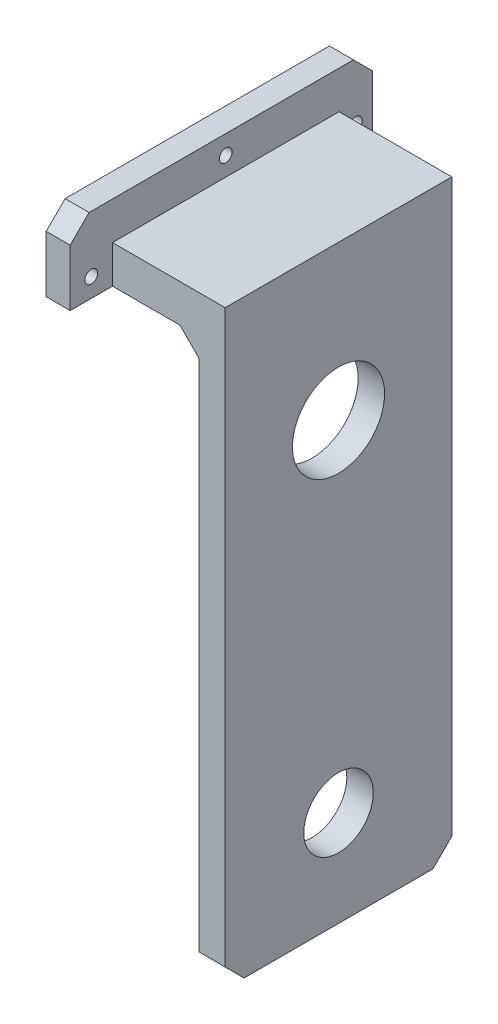
SolidWorks part; units mm, degrees
material "PLA"
ref_plane "Front Plane" through (0, 0, 0) normal (0, 0, 1) x (1, 0, 0)
ref_plane "Top Plane" through (0, 0, 0) normal (0, 1, 0) x (1, 0, 0)
ref_plane "Right Plane" through (0, 0, 0) normal (1, 0, 0) x (0, 0, -1)
sketch "Sketch1" plane through (0, 0, 0) normal (1, 0, 0) x (0, 0, -1)
  line L1 (-15, 2.5) -> (15, 2.5)
  line L2 (-15, 2.5) -> (-15, -2.5)
  line L3 (-15, -2.5) -> (15, -2.5)
  line L4 (15, 2.5) -> (15, -2.5)
  point P4 (0, 2.5)
  point P6 (-15, 0)
  dimension "D1" = 30
  dimension "D2" = 5
extrude "Boss-Extrude1" add sketch "Sketch1" along normal blind 18.1
sketch "Sketch2" plane through (0, 0, 0) normal (-1, 0, 0) x (0, 0, 1)
  line L0 (-20.4312, -2.5) -> (20.4312, -2.5) construction
  line L4 (15, 0) -> (20.5974, 0) construction
  line L5 (-19.4026, -2.5) -> (20.5974, -2.5)
  line L7 (-19.4026, 7.5) -> (20.5974, 7.5)
  line L8 (20.5974, -2.5) -> (20.5974, 7.5)
  line L9 (-19.4026, 7.5) -> (-19.4026, 2.5) construction
  line L11 (-19.4026, 7.5) -> (-19.4026, -2.5)
  line L12 (-19.4026, 0) -> (-15, 0) construction
  line L13 (-15, -2.5) -> (-15, 2.5) construction
  line L14 (15, 2.5) -> (15, -2.5) construction
  line L15 (-19.4026, 5) -> (0, 5) construction
  line L16 (20.5974, 5) -> (0, 5) construction
  circle A0 centre (-17.2013, 0) radius 0.85
  circle A1 centre (17.7987, 0) radius 0.85
  circle A5 centre (0, 5) radius 0.85
  point P3 (0, -2.5)
  point P6 (0, 2.5)
  point P12 (0, 0)
  dimension "D3" = 1.7
  dimension "D4" = 1.7
  dimension "D7" = 1.7
  dimension "D1" = 10
  dimension "D2" = 40
extrude "Boss-Extrude2" add sketch "Sketch2" against normal blind 3.175
sketch "Sketch3" plane through (0, -2.5, 0) normal (0, -1, 0) x (1, 0, 0)
  line L0 (18.1, -15) -> (3.175, -15) construction
  line L1 (18.1, 15) -> (14.6, 15)
  line L2 (18.1, 15) -> (18.1, -15)
  line L3 (18.1, -15) -> (14.6, -15)
  line L4 (14.6, 15) -> (14.6, -15)
  dimension "D1" = 3.5
extrude "Boss-Extrude3" add sketch "Sketch3" along normal blind 73.1
chamfer "Chamfer1" distance 2.5 angle 45 1 edges at (14.6, -2.5, 0)
chamfer "Chamfer2" distance 2.5 angle 45 2 edges at (1.5875, 7.5, -19.4026) (1.5875, 7.5, 20.5974)
sketch "Sketch4" plane through (18.1, 0, 0) normal (1, 0, 0) x (0, 0, -1)
  circle A0 centre (0, -17.9) radius 6.1
  circle A1 centre (0, -62.9) radius 4.6
  dimension "D1" = 12.2
  dimension "D2" = 9.2
extrude "Cut-Extrude1" cut sketch "Sketch4" against normal up to next
chamfer "Chamfer3" distance 2.5 angle 45 2 edges at (16.35, -75.6, -15) (16.35, -75.6, 15)
